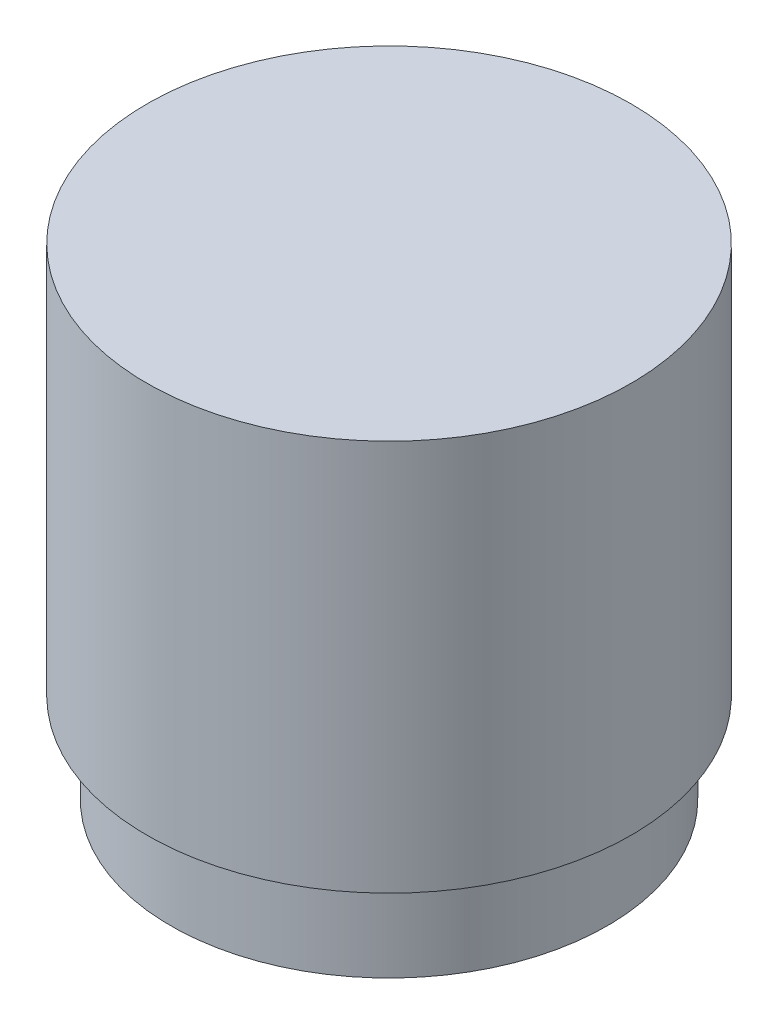
SolidWorks part; units mm, degrees
ref_plane "Front Plane" through (0, 0, 0) normal (0, 0, 1) x (1, 0, 0)
ref_plane "Top Plane" through (0, 0, 0) normal (0, 1, 0) x (1, 0, 0)
ref_plane "Right Plane" through (0, 0, 0) normal (1, 0, 0) x (0, 0, -1)
sketch "Sketch1" plane through (0, 0, 0) normal (0, 0, 1) x (1, 0, 0)
  line L0 (0, 0) -> (0, 24.2776) construction
  line L1 (-7.25, 0) -> (-7.25, 3)
  line L2 (-7.25, 3) -> (-8.04, 3)
  line L3 (-8.04, 3) -> (-8.04, 16)
  line L4 (-8.04, 16) -> (0, 16)
  line L5 (0, 16) -> (0, 13.57)
  line L6 (0, 13.57) -> (-2.91, 13.57)
  line L7 (-2.91, 13.57) -> (-2.91, 4.3)
  line L8 (-2.91, 4.3) -> (-6.375, 4.3)
  line L9 (-6.375, 4.3) -> (-6.375, 0)
  line L10 (-6.375, 0) -> (-7.25, 0)
  point P14 (-7.25, 4.437)
  dimension "D1" = 16.08
  dimension "D2" = 14.5
  dimension "D3" = 3
  dimension "D4" = 16
  dimension "D5" = 13.57
  dimension "D6" = 5.82
  dimension "D7" = 4.3
  dimension "D8" = 12.75
revolve "Revolve1" add sketch "Sketch1" angle 360 about L0
